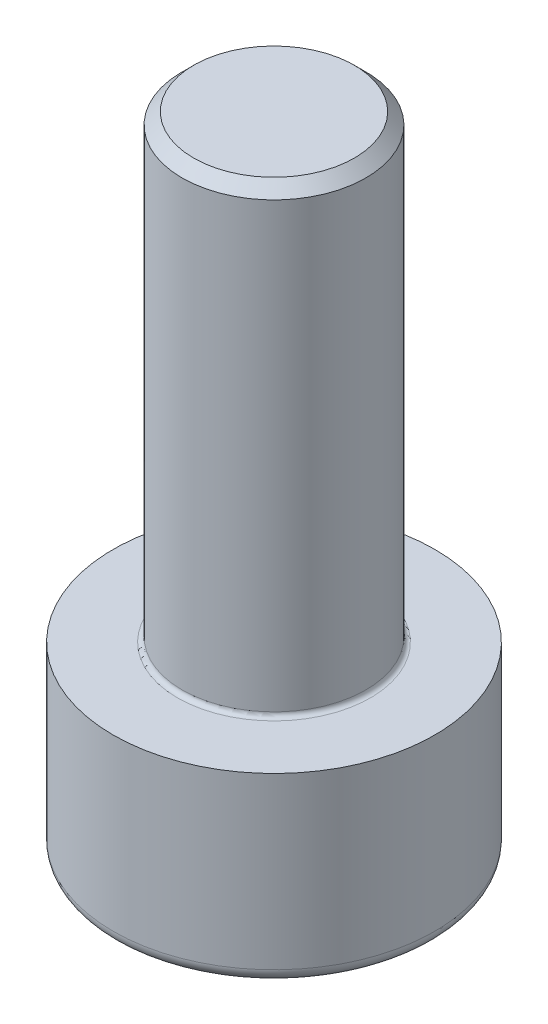
SolidWorks part; units mm, degrees
material "AISI 304"
ref_plane "前视基准面" through (0, 0, 0) normal (0, 0, 1) x (1, 0, 0)
ref_plane "上视基准面" through (0, 0, 0) normal (0, 1, 0) x (1, 0, 0)
ref_plane "右视基准面" through (0, 0, 0) normal (1, 0, 0) x (0, 0, -1)
other "Configuration Table"
sketch "草图1" plane through (0, 0, 0) normal (0, 0, 1) x (1, 0, 0)
  line L0 (0, 3.366) -> (0, 14)
  line L1 (0, 14) -> (1.75, 14)
  line L2 (1.75, 14) -> (2, 13.75)
  line L3 (2, 13.75) -> (2, 4.1)
  line L4 (2.1, 4) -> (3.5, 4)
  line L5 (3.5, 4) -> (3.5, 0.3)
  line L6 (3.2, 0) -> (1.5, 0)
  line L7 (1.5, 0) -> (1.5, 2.5)
  line L8 (1.5, 2.5) -> (0, 3.366)
  line L9 (0, 3.366) -> (0, 0) construction
  arc A0 (2, 4.1) -> (2.1, 4) centre (2.1, 4.1) ccw
  arc A1 (3.5, 0.3) -> (3.2, 0) centre (3.2, 0.3) cw
  dimension "D3" = 3
  dimension "r" = 0.1
  dimension "r2" = 0.3
  dimension "D1" = 1.5
  dimension "dk" = 7
  dimension "D2" = 120
  dimension "d" = 4
  dimension "k" = 4
  dimension "l" = 10
  dimension "内径" = 3.5
  dimension "D5" = 45
revolve "旋转1" add sketch "草图1" angle 360 about L9
sketch "草图2" plane through (0, 0, 0) normal (0, -1, 0) x (1, 0, 0)
  line L1 (1.5, -0.866) -> (1.5, 0.866)
  line L2 (1.5, 0.866) -> (0, 1.7321)
  line L3 (0, 1.7321) -> (-1.5, 0.866)
  line L4 (-1.5, 0.866) -> (-1.5, -0.866)
  line L5 (-1.5, -0.866) -> (0, -1.7321)
  line L6 (0, -1.7321) -> (1.5, -0.866)
  circle A0 centre (0, 0) radius 1.5 construction
  circle A1 centre (0, 0) radius 1.5 construction
extrude "切除-拉伸1" cut sketch "草图2" against normal up to surface (2.366 mm away)
